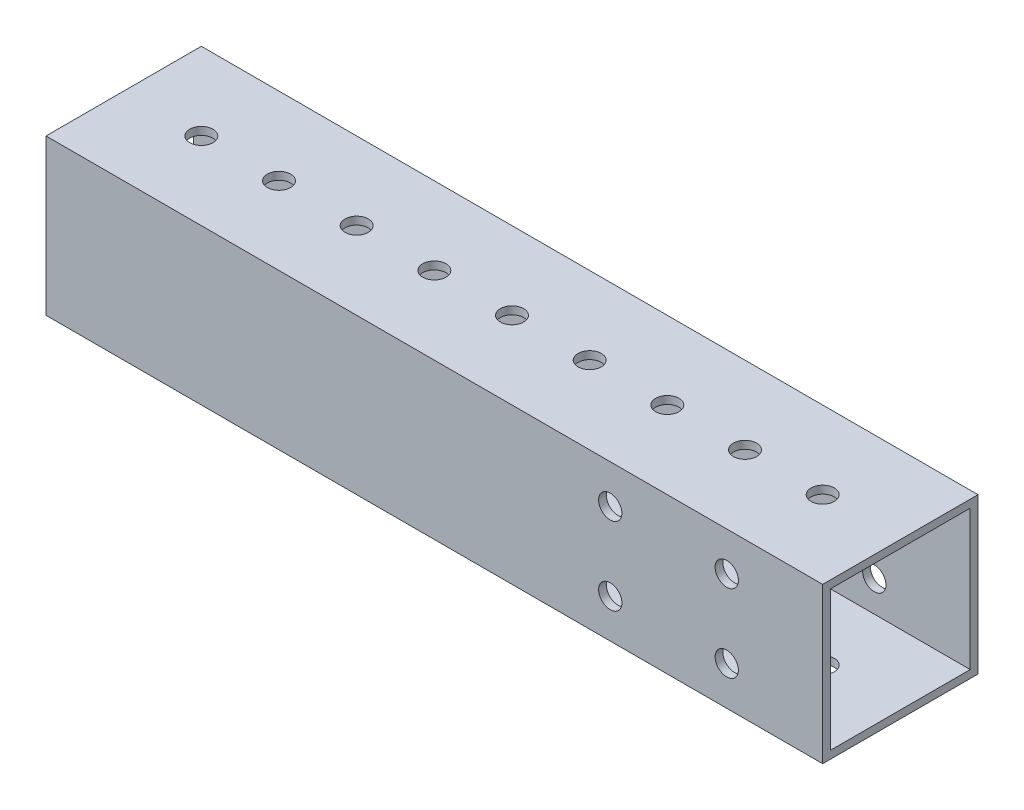
SolidWorks part; units mm, degrees
ref_plane "前视基准面" through (0, 0, 0) normal (0, 0, 1) x (1, 0, 0)
ref_plane "上视基准面" through (0, 0, 0) normal (0, 1, 0) x (1, 0, 0)
ref_plane "右视基准面" through (0, 0, 0) normal (1, 0, 0) x (0, 0, -1)
other "Configuration Table"
sketch "草图1" plane through (0, 0, 0) normal (1, 0, 0) x (0, 0, -1)
  line L0 (-1, 19) -> (-19, 19)
  line L1 (0, 0) -> (-20, 0)
  line L2 (0, 0) -> (0, 20)
  line L3 (0, 20) -> (-20, 20)
  line L4 (-20, 0) -> (-20, 20)
  line L5 (-19, 1) -> (-19, 19)
  line L6 (-1, 1) -> (-19, 1)
  line L7 (-1, 1) -> (-1, 19)
  dimension "D1" = 20
  dimension "D2" = 20
  dimension "D3" = 1
extrude "凸台-拉伸1" add sketch "草图1" along normal blind 100
sketch "草图2" plane through (0, 0, 20) normal (0, 0, 1) x (1, 0, 0)
  line L0 (100, 20) -> (0, 20) construction
  line L1 (100, 20) -> (100, 0) construction
  line L2 (50, 20) -> (50, 0) construction
  line L3 (100, 0) -> (0, 0) construction
  line L4 (0, 10) -> (100, 10) construction
  line L5 (0, 20) -> (0, 0) construction
  circle A0 centre (72.65, 15) radius 1.5
  circle A2 centre (72.65, 5) radius 1.5
  circle A4 centre (87.65, 15) radius 1.5
  circle A5 centre (87.65, 5) radius 1.5
  dimension "D1" = 3
  dimension "D2" = 10
  dimension "D3" = 12.35
  dimension "D5" = 15
  dimension "D4" = 2
extrude "切除-拉伸1" cut sketch "草图2" against normal through all
sketch "草图3" plane through (0, 20, 0) normal (0, 1, 0) x (1, 0, 0)
  line L0 (125.7542, -10) -> (-25.0722, -10) construction
  line L1 (100, -20) -> (0, -20) construction
  line L2 (100, 0) -> (0, 0) construction
  line L3 (100, 0) -> (100, -20) construction
  circle A0 centre (90, -10) radius 1.5
  circle A1 centre (80, -10) radius 1.5
  circle A2 centre (70, -10) radius 1.5
  circle A3 centre (60, -10) radius 1.5
  circle A4 centre (50, -10) radius 1.5
  circle A5 centre (40, -10) radius 1.5
  circle A6 centre (30, -10) radius 1.5
  circle A7 centre (20, -10) radius 1.5
  circle A8 centre (10, -10) radius 1.5
  dimension "D1" = 3
  dimension "D2" = 10
  dimension "D4" = 10
  dimension "D3" = 9
extrude "切除-拉伸2" cut sketch "草图3" against normal through all
